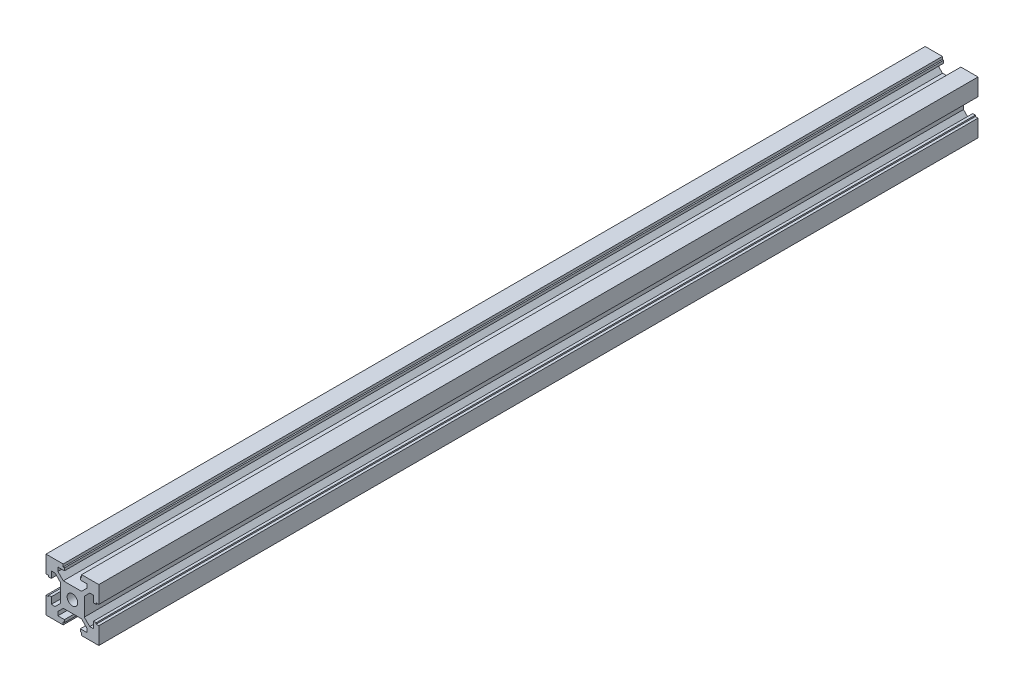
SolidWorks part; units mm, degrees
ref_plane "Front Plane" through (0, 0, 0) normal (0, 0, 1) x (1, 0, 0)
ref_plane "Top Plane" through (0, 0, 0) normal (0, 1, 0) x (1, 0, 0)
ref_plane "Right Plane" through (0, 0, 0) normal (1, 0, 0) x (0, 0, -1)
sketch "Sketch1" plane through (0, 0, 0) normal (0, 0, 1) x (1, 0, 0)
  line L0 (0, 10) -> (0, -4.5007) construction
  line L1 (-10, -10) -> (-3.5, -10)
  line L2 (-10, -10) -> (-10, -3.5)
  line L3 (-10, 10) -> (-3.5, 10)
  line L4 (10, -10) -> (10, -3.5)
  line L5 (-10, -10) -> (10, 10) construction
  line L6 (-10, 10) -> (10, -10) construction
  line L7 (-10, 0) -> (10, 0) construction
  line L8 (-3.5, 10) -> (-3.5, 9)
  line L9 (-3.44, -4.5007) -> (3.44, -4.5007)
  line L10 (-4.5007, -3.44) -> (-4.5007, 3.44)
  line L11 (-3.44, 4.5007) -> (3.44, 4.5007)
  line L12 (4.5007, -3.44) -> (4.5007, 3.44)
  line L13 (-10, -10) -> (10, 10) construction
  line L14 (-10, 10) -> (10, -10) construction
  line L15 (-3.5, 9) -> (-3, 9)
  line L16 (-3, 9) -> (-3, 8)
  line L17 (-3, 8) -> (-5.5, 8)
  line L18 (-5.5, 8) -> (-5.5, 6.5607)
  line L19 (-5.5, 6.5607) -> (-3.44, 4.5007)
  line L20 (3.5, 10) -> (10, 10)
  line L21 (3.5, 9) -> (3, 9)
  line L22 (5.5, 6.5607) -> (3.44, 4.5007)
  line L23 (5.5, 8) -> (5.5, 6.5607)
  line L24 (3, 8) -> (5.5, 8)
  line L25 (3, 9) -> (3, 8)
  line L26 (3.5, 10) -> (3.5, 9)
  line L27 (-3.5, 10) -> (3.5, 10) construction
  line L28 (5.5, -6.5607) -> (3.44, -4.5007)
  line L29 (5.5, -8) -> (5.5, -6.5607)
  line L30 (3, -8) -> (5.5, -8)
  line L31 (3, -9) -> (3, -8)
  line L32 (3.5, -9) -> (3, -9)
  line L33 (3.5, -10) -> (3.5, -9)
  line L34 (-3.5, -9) -> (-3, -9)
  line L35 (-5.5, -6.5607) -> (-3.44, -4.5007)
  line L36 (-5.5, -8) -> (-5.5, -6.5607)
  line L37 (-3, -8) -> (-5.5, -8)
  line L38 (-3, -9) -> (-3, -8)
  line L39 (-3.5, -10) -> (-3.5, -9)
  line L40 (-6.5607, -5.5) -> (-4.5007, -3.44)
  line L41 (-8, -5.5) -> (-6.5607, -5.5)
  line L42 (-8, -3) -> (-8, -5.5)
  line L43 (-10, -3.5) -> (-9, -3.5)
  line L44 (-9, -3) -> (-8, -3)
  line L45 (-9, -3.5) -> (-9, -3)
  line L46 (6.5607, -5.5) -> (4.5007, -3.44)
  line L47 (8, -5.5) -> (6.5607, -5.5)
  line L48 (8, -3) -> (8, -5.5)
  line L49 (9, -3) -> (8, -3)
  line L50 (9, -3.5) -> (9, -3)
  line L51 (10, -3.5) -> (9, -3.5)
  line L52 (-6.5607, 5.5) -> (-4.5007, 3.44)
  line L53 (-8, 5.5) -> (-6.5607, 5.5)
  line L54 (-8, 3) -> (-8, 5.5)
  line L55 (-9, 3) -> (-8, 3)
  line L56 (-9, 3.5) -> (-9, 3)
  line L57 (-10, 3.5) -> (-9, 3.5)
  line L58 (10, 3.5) -> (9, 3.5)
  line L59 (9, 3.5) -> (9, 3)
  line L60 (9, 3) -> (8, 3)
  line L61 (8, 3) -> (8, 5.5)
  line L62 (8, 5.5) -> (6.5607, 5.5)
  line L63 (6.5607, 5.5) -> (4.5007, 3.44)
  line L64 (10, 3.5) -> (10, 10)
  line L65 (-10, 3.5) -> (-10, 10)
  line L66 (-10, 3.5) -> (-10, -3.5) construction
  line L67 (10, 3.5) -> (10, -3.5) construction
  line L68 (3.5, -10) -> (10, -10)
  line L69 (-3.5, -10) -> (3.5, -10) construction
  circle A0 centre (0, 0) radius 2
  point P0 (0, 0)
  point P10 (0, 0)
  dimension "D10" = 4
  dimension "D1" = 20
  dimension "D2" = 14.5007
  dimension "D3" = 0.75
  dimension "D4" = 3.5
  dimension "D5" = 3
  dimension "D6" = 1
  dimension "D7" = 1
  dimension "D8" = 3.44
  dimension "D9" = 5.5
extrude "Boss-Extrude1" add sketch "Sketch1" along normal blind 333
